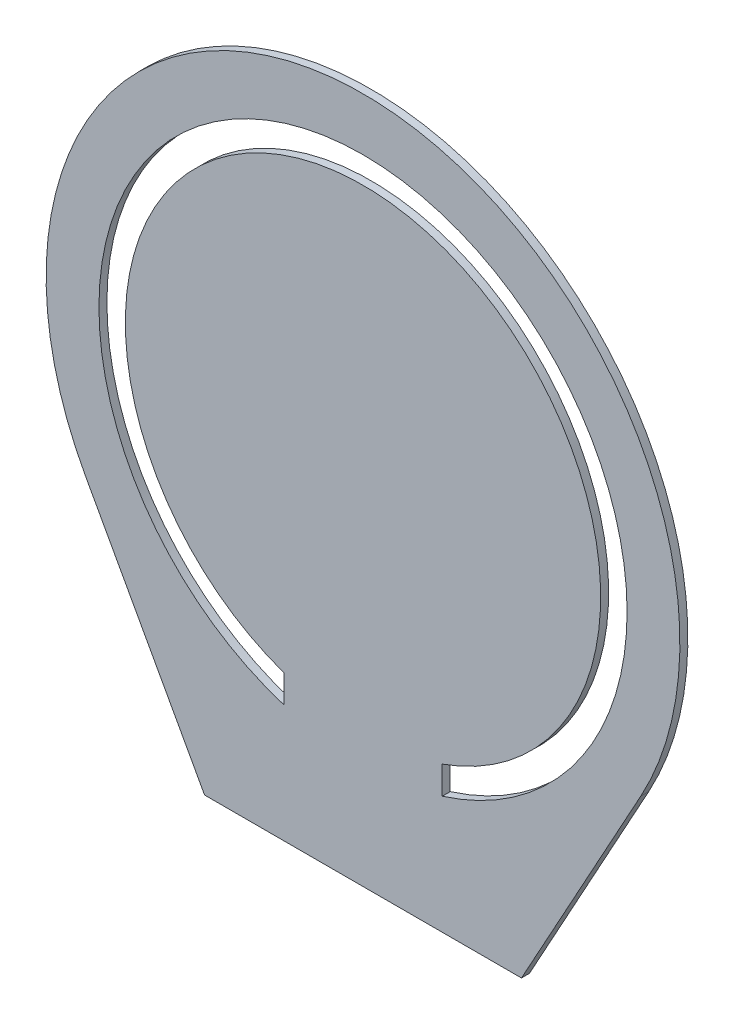
SolidWorks part; units mm, degrees
ref_plane "Plano frontal" through (0, 0, 0) normal (0, 0, 1) x (1, 0, 0)
ref_plane "Plano superior" through (0, 0, 0) normal (0, 1, 0) x (1, 0, 0)
ref_plane "Plano direito" through (0, 0, 0) normal (1, 0, 0) x (0, 0, -1)
sketch "Sketch1" plane through (0, 0, 0) normal (0, 0, 1) x (1, 0, 0)
  line L0 (-15, -35) -> (-7.5, -35)
  line L1 (-15, -35) -> (15, -35)
  line L4 (-15, -35) -> (-7.5, -35)
  line L5 (0, 0) -> (0, -35)
  line L7 (15, -35) -> (26.2929, -14.4459)
  line L9 (-7.5, -23.8485) -> (-7.5, -21.2132)
  line L12 (7.5, -23.8485) -> (7.5, -21.2132)
  line L16 (-15, -35) -> (-26.2929, -14.4459)
  line L17 (-15, -35) -> (-5, -35)
  line L19 (-20.4038, -14.4459) -> (-9.1109, -35)
  arc A0 (7.5, -21.2132) -> (-7.5, -21.2132) centre (0, 0) ccw
  arc A1 (7.5, -23.8485) -> (-7.5, -23.8485) centre (0, 0) ccw
  arc A2 (26.2929, -14.4459) -> (-26.2929, -14.4459) centre (0, 0) ccw
  point P10 (0, -35)
  dimension "D1" = 45
  dimension "D2" = 50
  dimension "D3" = 60
  dimension "D5" = 30
  dimension "D6" = 7.5
  dimension "D8" = 2.6353
  dimension "D9" = 35
  dimension "D10" = 10
  dimension "D11" = 5.8891
  dimension "D12" = 5.8891
extrude "Boss-Extrude1" add sketch "Sketch1" along normal blind 0.7544
